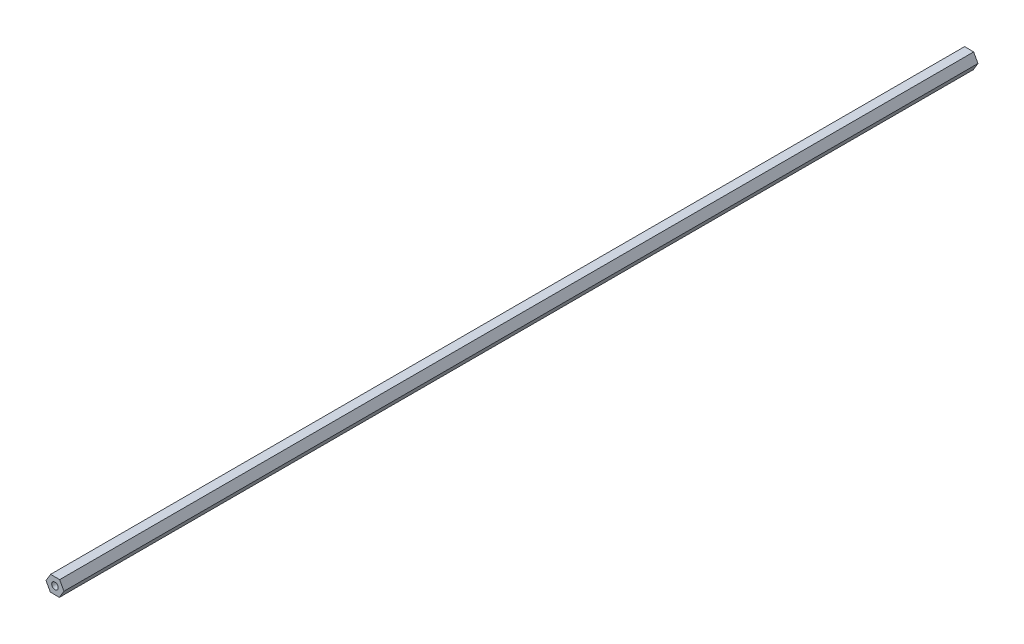
SolidWorks part; units mm, degrees
ref_plane "Front Plane" through (0, 0, 0) normal (0, 0, 1) x (1, 0, 0)
ref_plane "Top Plane" through (0, 0, 0) normal (0, 1, 0) x (1, 0, 0)
ref_plane "Right Plane" through (0, 0, 0) normal (1, 0, 0) x (0, 0, -1)
sketch "Sketch1" plane through (0, 0, 0) normal (0, 0, 1) x (1, 0, 0)
  line L1 (3.5548, -6.413) -> (7.3312, -0.128)
  line L2 (7.3312, -0.128) -> (3.7764, 6.285)
  line L3 (3.7764, 6.285) -> (-3.5548, 6.413)
  line L4 (-3.5548, 6.413) -> (-7.3312, 0.128)
  line L5 (-7.3312, 0.128) -> (-3.7764, -6.285)
  line L6 (-3.7764, -6.285) -> (3.5548, -6.413)
  circle A0 centre (0, 0) radius 6.35 construction
  circle A1 centre (0, 0) radius 2.667
  dimension "D1" = 12.7
extrude "Boss-Extrude1" add sketch "Sketch1" along normal blind 746.76
